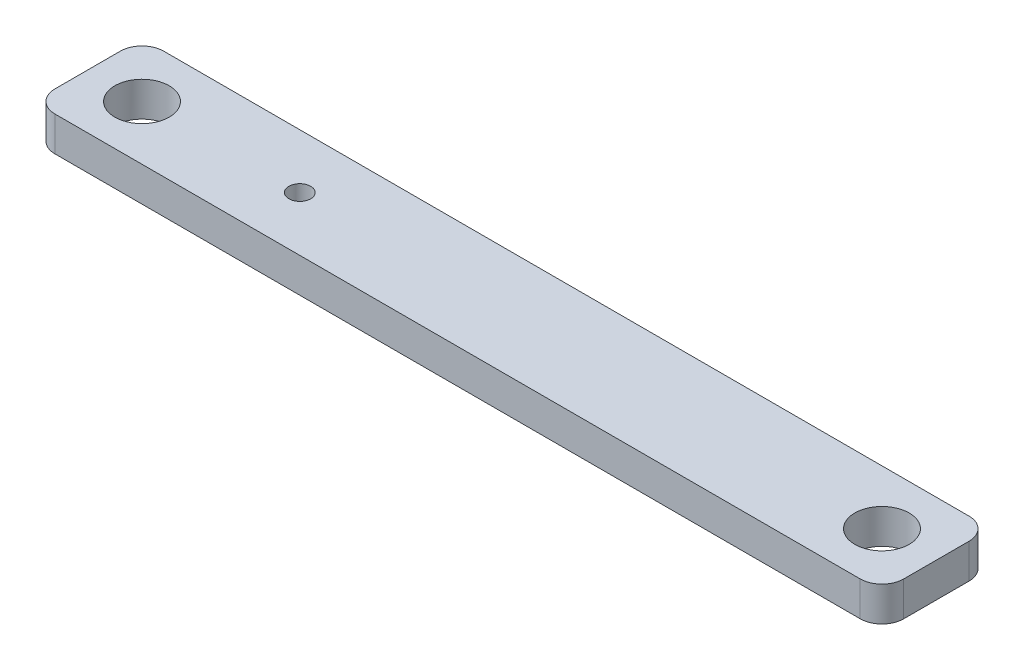
SolidWorks part; units mm, degrees
ref_plane "Front Plane" through (0, 0, 0) normal (0, 0, 1) x (1, 0, 0)
ref_plane "Top Plane" through (0, 0, 0) normal (0, 1, 0) x (1, 0, 0)
ref_plane "Right Plane" through (0, 0, 0) normal (1, 0, 0) x (0, 0, -1)
sketch "Sketch2" plane through (0, 0, 0) normal (0, 1, 0) x (1, 0, 0)
  line L1 (-39, -5) -> (39, -5)
  line L2 (-39, -5) -> (-39, 5)
  line L3 (-39, 5) -> (39, 5)
  line L4 (39, -5) -> (39, 5)
  line L5 (-39, -5) -> (39, 5) construction
  line L6 (-39, 5) -> (39, -5) construction
  point P0 (0, 0)
  dimension "D1" = 78
  dimension "D2" = 10
extrude "Boss-Extrude1" add sketch "Sketch2" along normal blind 3.175
sketch "Sketch3" plane through (0, 3.175, 0) normal (0, 1, 0) x (1, 0, 0)
  line L0 (-64.0944, 0) -> (61.2196, 0) construction
  line L1 (0, 21.5935) -> (0, -26.8203) construction
  circle A0 centre (-34, 0) radius 2.5
  circle A1 centre (34, 0) radius 2.5
  dimension "D1" = 5
  dimension "D2" = 34
extrude "Cut-Extrude1" cut sketch "Sketch3" against normal up to surface (3.175 mm away) up to face at (0, 0, 0)
sketch "Sketch4" plane through (0, 3.175, 0) normal (0, 1, 0) x (1, 0, 0)
  line L0 (-39, 0) -> (0, 0) construction
  line L3 (-39, 5) -> (-39, -5) construction
  circle A0 centre (-19.5, 0) radius 1
  dimension "D1" = 2
extrude "Cut-Extrude2" cut sketch "Sketch4" against normal up to next
fillet "Fillet1" radius 2 4 edges at (39, 1.5875, 5) (39, 1.5875, -5) (-39, 1.5875, -5) (-39, 1.5875, 5)
